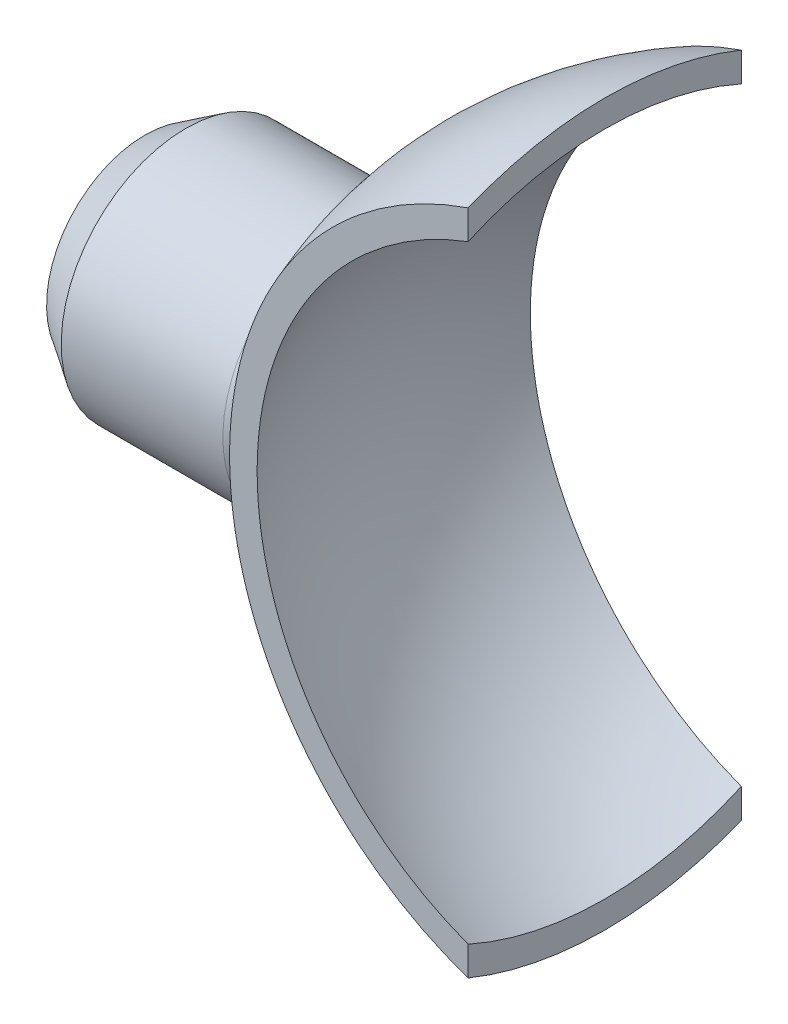
SolidWorks part; units mm, degrees
material "1023 Karbon Çeliği Levha (SS)"
ref_plane "Ön Düzlem" through (0, 0, 0) normal (0, 0, 1) x (1, 0, 0)
ref_plane "Üst Düzlem" through (0, 0, 0) normal (0, 1, 0) x (1, 0, 0)
ref_plane "Sağ Düzlem" through (0, 0, 0) normal (1, 0, 0) x (0, 0, -1)
sketch "Çizim1" plane through (0, 0, 0) normal (0, 0, 1) x (1, 0, 0)
  line L0 (-1.3251, 2.1396) -> (-1.3251, 0.5703)
  line L1 (-1.3251, 0.5703) -> (-0.4112, 0.5703)
  line L9 (7.0981, 9.9227) -> (7.0981, 10.7232)
  line L10 (-0.5588, 3.7071) -> (-5.3675, 3.7071)
  line L11 (-5.3675, 3.7071) -> (-6.5817, 2.9288)
  line L12 (-6.5817, 2.9288) -> (-6.5817, 2.1452)
  line L13 (-6.5817, 2.1452) -> (-1.3251, 2.1396)
  line L14 (0, 0) -> (-0.4261, 0)
  arc A0 (-0.4112, 0.5703) -> (-0.4261, 0) centre (10.4848, 0) ccw
  arc A3 (7.0981, 9.9227) -> (0, 0) centre (10.4848, 0) ccw
  arc A4 (7.0981, 10.7232) -> (-0.1818, 3.5611) centre (10.4848, 0) ccw
  arc A5 (-0.1818, 3.5611) -> (-0.5588, 3.7071) centre (-0.5779, 3.098) ccw
revolve "Döndür3" add sketch "Çizim1" angle 360 about L14
sketch "Çizim2" plane through (-6.5817, 0, 0) normal (-1, 0, 0) x (0, 0, 1)
  line L2 (-4.065, 0) -> (-4.065, 9.9228)
  line L3 (-4.065, 0) -> (-4.065, -10.8542)
  line L4 (4.065, 0) -> (4.065, 10.5127)
  line L5 (4.065, 0) -> (4.065, -11.3492)
  line L6 (4.065, -11.3492) -> (12.606, -11.3492)
  line L7 (12.606, -11.3492) -> (12.1481, 10.5127)
  line L8 (12.1481, 10.5127) -> (4.065, 10.5127)
  line L9 (-4.065, 9.9228) -> (-12.2776, 10.1104)
  line L10 (-12.2776, 10.1104) -> (-12.2776, -10.8542)
  line L11 (-12.2776, -10.8542) -> (-4.065, -10.8542)
  circle A0 centre (0, 0) radius 10.7232 construction
extrude "Kes-Ekstrüzyon1" cut sketch "Çizim2" against normal blind 18
